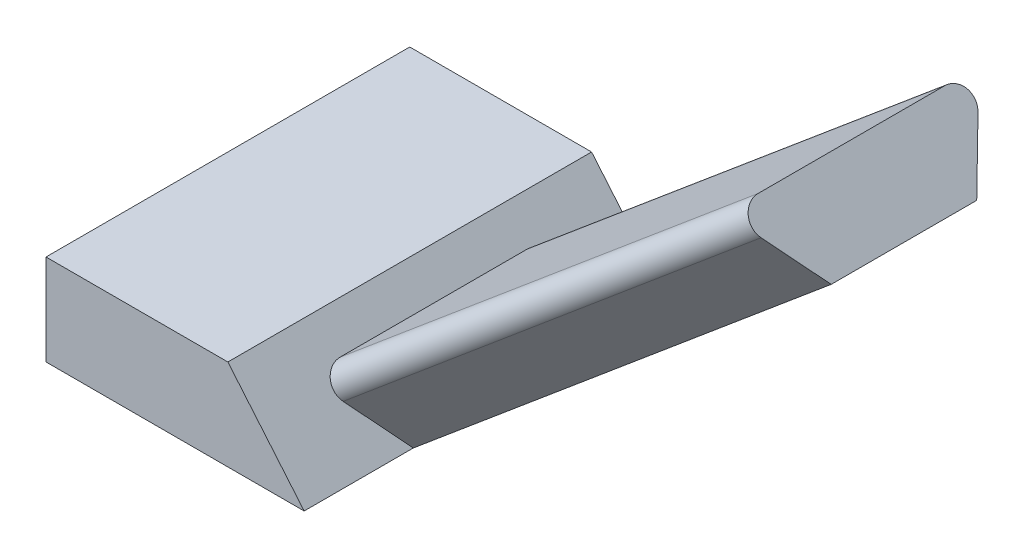
SolidWorks part; units mm, degrees
ref_plane "Front Plane" through (0, 0, 0) normal (0, 0, 1) x (1, 0, 0)
ref_plane "Top Plane" through (0, 0, 0) normal (0, 1, 0) x (1, 0, 0)
ref_plane "Right Plane" through (0, 0, 0) normal (1, 0, 0) x (0, 0, -1)
sketch "Sketch1" plane through (0, 0, 0) normal (0, 0, 1) x (1, 0, 0)
sketch "Sketch3" plane through (0, 0, 0) normal (0, 0, 1) x (1, 0, 0)
  line L0 (0, 0) -> (0, 5)
  line L1 (0, 5) -> (10, 5)
  line L5 (14.1955, 0) -> (0, 0)
  line L6 (10, 5) -> (14.1955, 0)
  dimension "D1" = 5
  dimension "D2" = 50
  dimension "D3" = 10
extrude "Boss-Extrude2" add sketch "Sketch3" along normal mid plane 20
sketch "Sketch5" plane through (8.3303, 6.9899, 0) normal (0.766, 0.6428, 0) x (0, 0, -1)
  line L0 (-4, -9.1247) -> (-5.9635, -6.1794)
  line L1 (-10, -9.1247) -> (10, -9.1247) construction
  line L3 (-5.1315, -4.6247) -> (5.1315, -4.6247)
  line L4 (5.9635, -6.1794) -> (4, -9.1247)
  line L5 (4, -9.1247) -> (-4, -9.1247)
  arc A0 (5.1315, -4.6247) -> (5.9635, -6.1794) centre (5.1315, -5.6247) cw
  arc A1 (-5.9635, -6.1794) -> (-5.1315, -4.6247) centre (-5.1315, -5.6247) cw
  point P8 (0, -9.1247)
  point P14 (7, -4.6247)
  point P17 (-7, -4.6247)
  dimension "D4" = 1
  dimension "D1" = 14
  dimension "D2" = 8
  dimension "D3" = 4.5
extrude "Boss-Extrude4" add sketch "Sketch5" along normal blind 30
